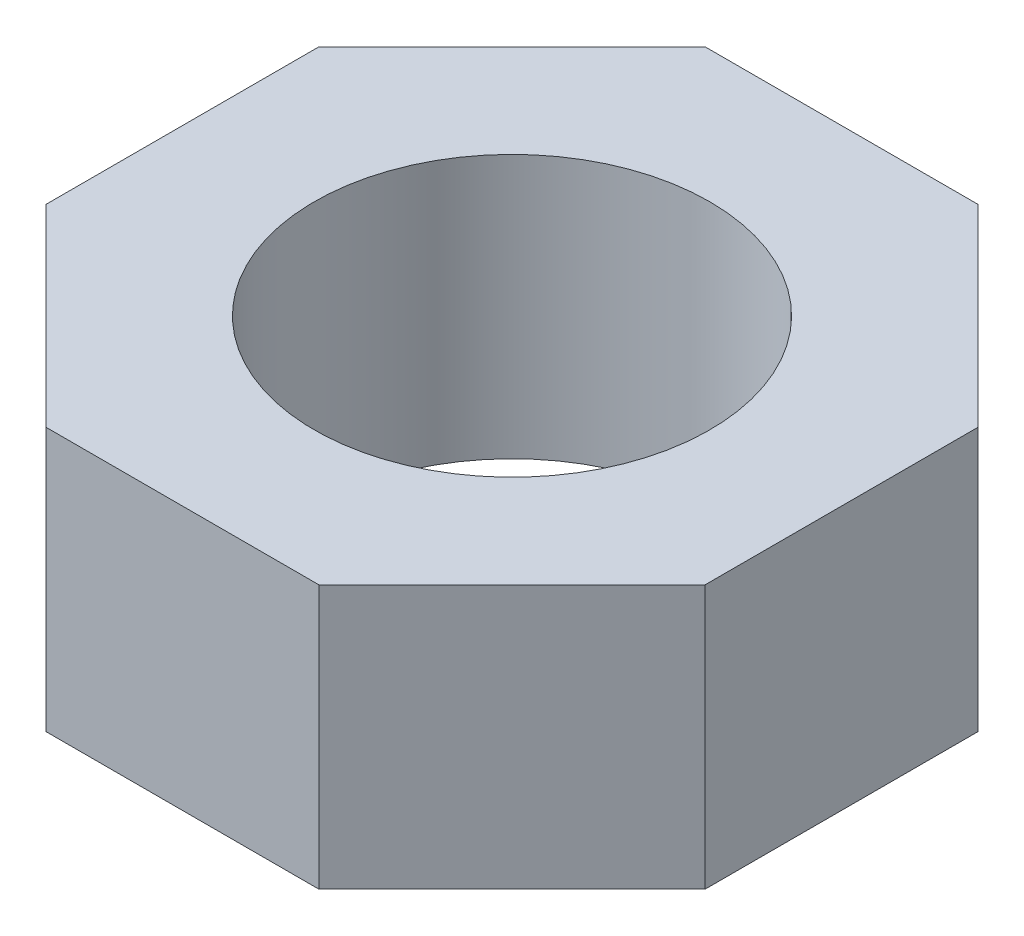
SolidWorks part; units mm, degrees
ref_plane "Plan de face" through (0, 0, 0) normal (0, 0, 1) x (1, 0, 0)
ref_plane "Plan de dessus" through (0, 0, 0) normal (0, 1, 0) x (1, 0, 0)
ref_plane "Plan de droite" through (0, 0, 0) normal (1, 0, 0) x (0, 0, -1)
sketch "Esquisse1" plane through (0, 0, 0) normal (0, 1, 0) x (1, 0, 0)
  line L0 (-1.0355, 2.5) -> (1.0355, 2.5)
  line L1 (1.0355, 2.5) -> (2.5, 1.0355)
  line L2 (2.5, 1.0355) -> (2.5, -1.0355)
  line L3 (2.5, -1.0355) -> (1.0355, -2.5)
  line L4 (1.0355, -2.5) -> (-1.0355, -2.5)
  line L5 (-1.0355, -2.5) -> (-2.5, -1.0355)
  line L6 (-2.5, -1.0355) -> (-2.5, 1.0355)
  line L7 (-2.5, 1.0355) -> (-1.0355, 2.5)
  line L8 (0, 2.5) -> (0, -2.5) construction
  dimension "D1" = 5
extrude "Extrusion1" add sketch "Esquisse1" along normal mid plane 2
sketch "Esquisse3" plane through (0, -1, 0) normal (0, -1, 0) x (1, 0, 0)
  circle A0 centre (0, 0) radius 1.5
  dimension "D1" = 3
extrude "Enlèv. mat.-Extru.1" cut sketch "Esquisse3" against normal through all
